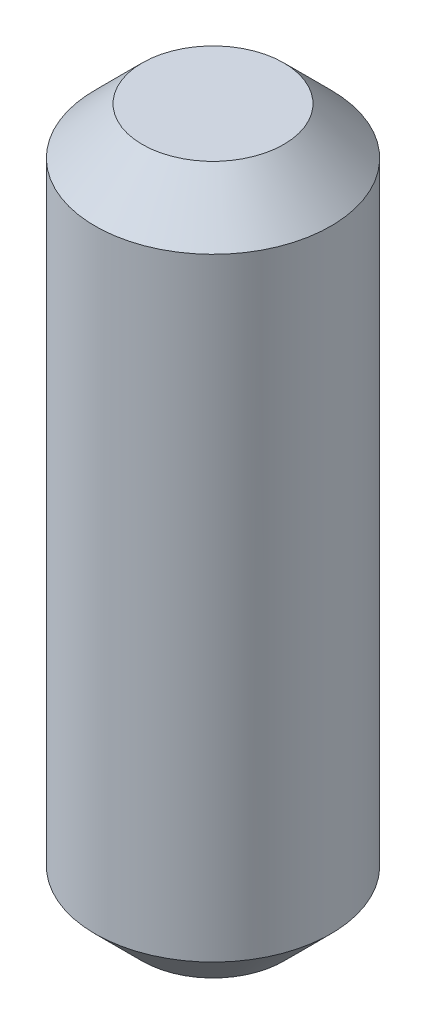
SolidWorks part; units mm, degrees
material "Plain Carbon Steel"
ref_plane "Front Plane" through (0, 0, 0) normal (0, 0, 1) x (1, 0, 0)
ref_plane "Top Plane" through (0, 0, 0) normal (0, 1, 0) x (1, 0, 0)
ref_plane "Right Plane" through (0, 0, 0) normal (1, 0, 0) x (0, 0, -1)
sketch "Sketch1" plane through (0, 0, 0) normal (0, 1, 0) x (1, 0, 0)
  circle A0 centre (0, 0) radius 3.175
  dimension "D1" = 6.35
extrude "Boss-Extrude1" add sketch "Sketch1" along normal blind 19.05
chamfer "Chamfer1" distance 1.27 angle 45 2 edges at (0, 0, 3.175) (0, 19.05, 3.175)
